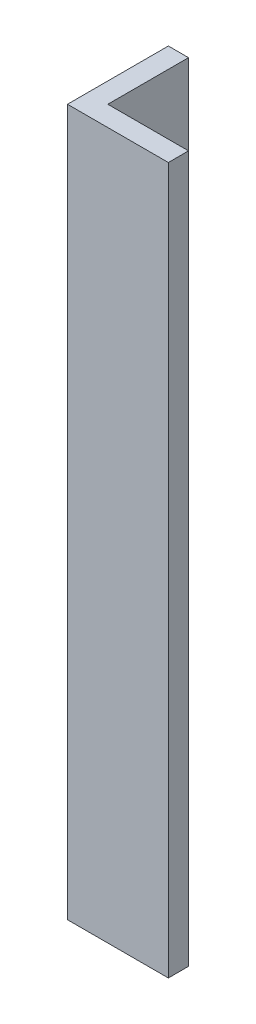
SolidWorks part; units mm, degrees
ref_plane "前视基准面" through (0, 0, 0) normal (0, 0, 1) x (1, 0, 0)
ref_plane "上视基准面" through (0, 0, 0) normal (0, 1, 0) x (1, 0, 0)
ref_plane "右视基准面" through (0, 0, 0) normal (1, 0, 0) x (0, 0, -1)
sketch "草图1" plane through (0, 0, 0) normal (0, 1, 0) x (1, 0, 0)
  line L0 (0, 0) -> (10, 0)
  line L1 (10, 0) -> (10, 2)
  line L2 (10, 2) -> (2, 2)
  line L3 (2, 2) -> (2, 10)
  line L4 (2, 10) -> (0, 10)
  line L5 (0, 10) -> (0, 0)
  dimension "D1" = 10
  dimension "D2" = 10
  dimension "D3" = 2
  dimension "D4" = 2
extrude "凸台-拉伸1" add sketch "草图1" along normal blind 70
